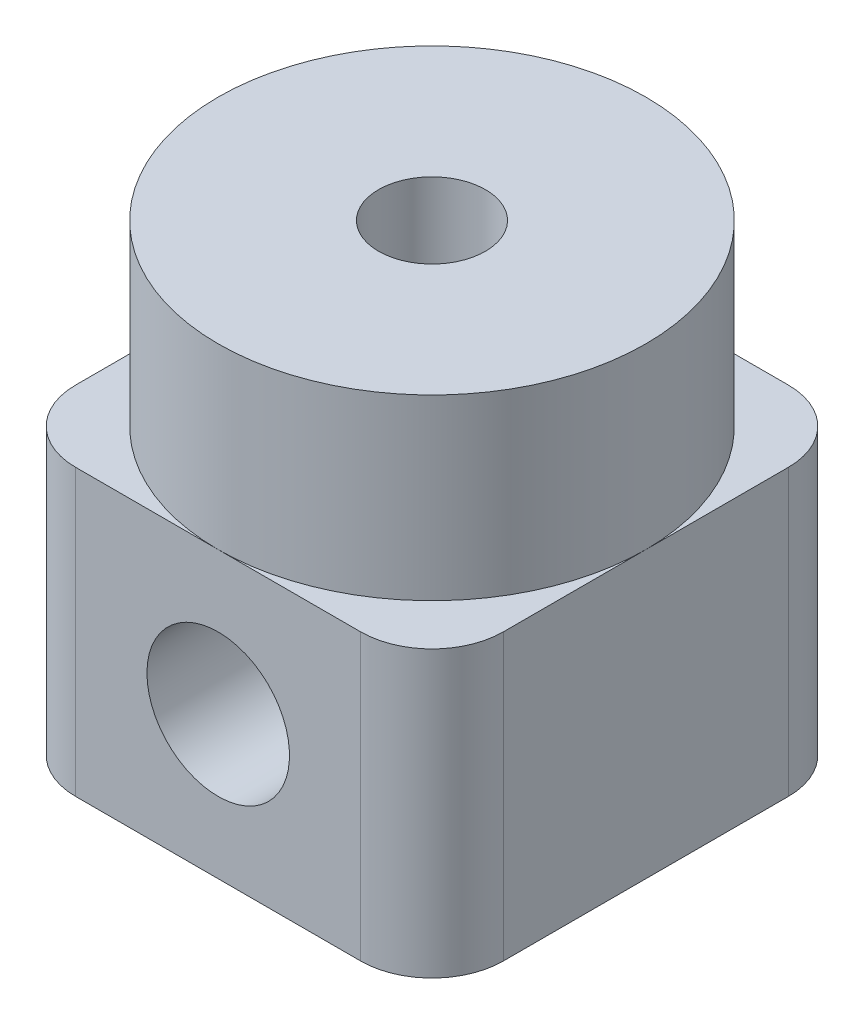
SolidWorks part; units mm, degrees
ref_plane "前视基准面" through (0, 0, 0) normal (0, 0, 1) x (1, 0, 0)
ref_plane "上视基准面" through (0, 0, 0) normal (0, 1, 0) x (1, 0, 0)
ref_plane "右视基准面" through (0, 0, 0) normal (1, 0, 0) x (0, 0, -1)
other "Configuration Table"
sketch "草图1" plane through (0, 0, 0) normal (0, 1, 0) x (1, 0, 0)
  circle A0 centre (0, 0) radius 6
  dimension "D1" = 12
extrude "凸台-拉伸1" add sketch "草图1" along normal blind 5
sketch "草图2" plane through (0, 0, 0) normal (0, -1, 0) x (1, 0, 0)
  line L1 (6, -6) -> (-6, -6)
  line L2 (6, -6) -> (6, 6)
  line L3 (6, 6) -> (-6, 6)
  line L4 (-6, -6) -> (-6, 6)
  line L5 (6, -6) -> (-6, 6) construction
  line L6 (6, 6) -> (-6, -6) construction
  point P0 (0, 0)
  dimension "D1" = 12
  dimension "D2" = 12
extrude "凸台-拉伸2" add sketch "草图2" along normal blind 8 contours L4 L3 L2 L1
fillet "圆角1" radius 2 4 edges at (-6, -4, -6) (6, -4, -6) (6, -4, 6) (-6, -4, 6)
sketch "草图3" plane through (0, 5, 0) normal (0, 1, 0) x (1, 0, 0)
  circle A0 centre (0, 0) radius 1.5
  dimension "D1" = 3
extrude "切除-拉伸1" cut sketch "草图3" against normal blind 5
sketch "草图4" plane through (0, 0, -6) normal (0, 0, -1) x (-1, 0, 0)
  line L0 (-4, 0) -> (0, 0) construction
  line L1 (-6, -8) -> (-6, 0) construction
  circle A0 centre (0, -4) radius 2
  dimension "D1" = 4
  dimension "D2" = 4
  dimension "D3" = 6
extrude "切除-拉伸2" cut sketch "草图4" against normal through all
